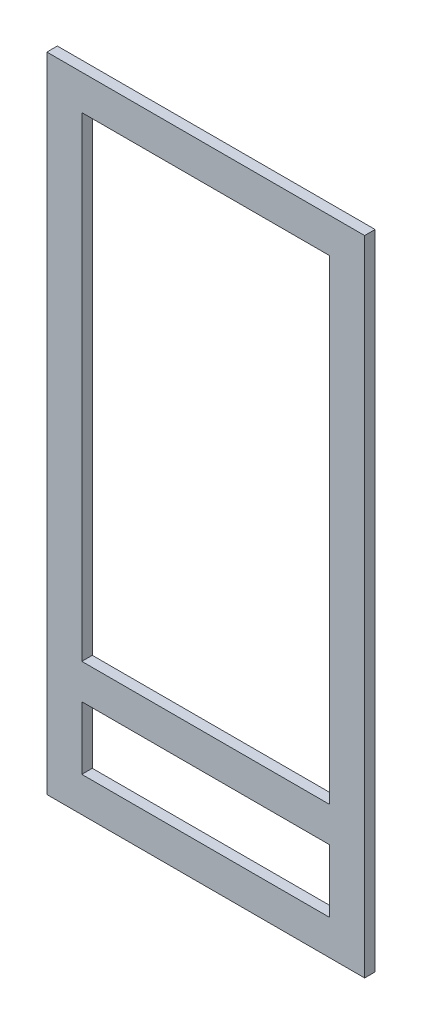
SolidWorks part; units mm, degrees
ref_plane "Alzado" through (0, 0, 0) normal (0, 0, 1) x (1, 0, 0)
ref_plane "Planta" through (0, 0, 0) normal (0, 1, 0) x (1, 0, 0)
ref_plane "Vista lateral" through (0, 0, 0) normal (1, 0, 0) x (0, 0, -1)
sketch "Croquis1" plane through (0, 0, 0) normal (0, 0, 1) x (1, 0, 0)
  line L1 (-227.35, 460) -> (227.35, 460)
  line L2 (-227.35, 460) -> (-227.35, -460)
  line L3 (-227.35, -460) -> (227.35, -460)
  line L4 (227.35, 460) -> (227.35, -460)
  line L5 (-227.35, 460) -> (227.35, -460) construction
  line L6 (-227.35, -460) -> (227.35, 460) construction
  line L7 (-177.35, 410) -> (177.35, 410)
  line L8 (-177.35, 410) -> (-177.35, -270)
  line L9 (-177.35, -270) -> (177.35, -270)
  line L10 (177.35, 410) -> (177.35, -270)
  point P0 (0, 0)
  dimension "D1" = 454.7
  dimension "D2" = 920
  dimension "D3" = 50
  dimension "D4" = 50
  dimension "D5" = 50
  dimension "D6" = 190
  dimension "D7" = 354.7
extrude "Saliente-Extruir1" add sketch "Croquis1" against normal blind 15
sketch "Croquis2" plane through (0, 0, 0) normal (0, 0, 1) x (1, 0, 0)
  line L0 (-177.35, 410) -> (-177.35, -270) construction
  line L1 (-177.35, -320) -> (177.35, -320)
  line L2 (-177.35, -320) -> (-177.35, -410)
  line L3 (-177.35, -410) -> (177.35, -410)
  line L4 (177.35, -320) -> (177.35, -410)
  line L5 (177.35, -270) -> (177.35, 410) construction
  line L6 (-177.35, -270) -> (177.35, -270) construction
  line L7 (-227.35, -460) -> (227.35, -460) construction
  dimension "D1" = 50
  dimension "D2" = 50
extrude "Cortar-Extruir1" cut sketch "Croquis2" against normal blind 15
